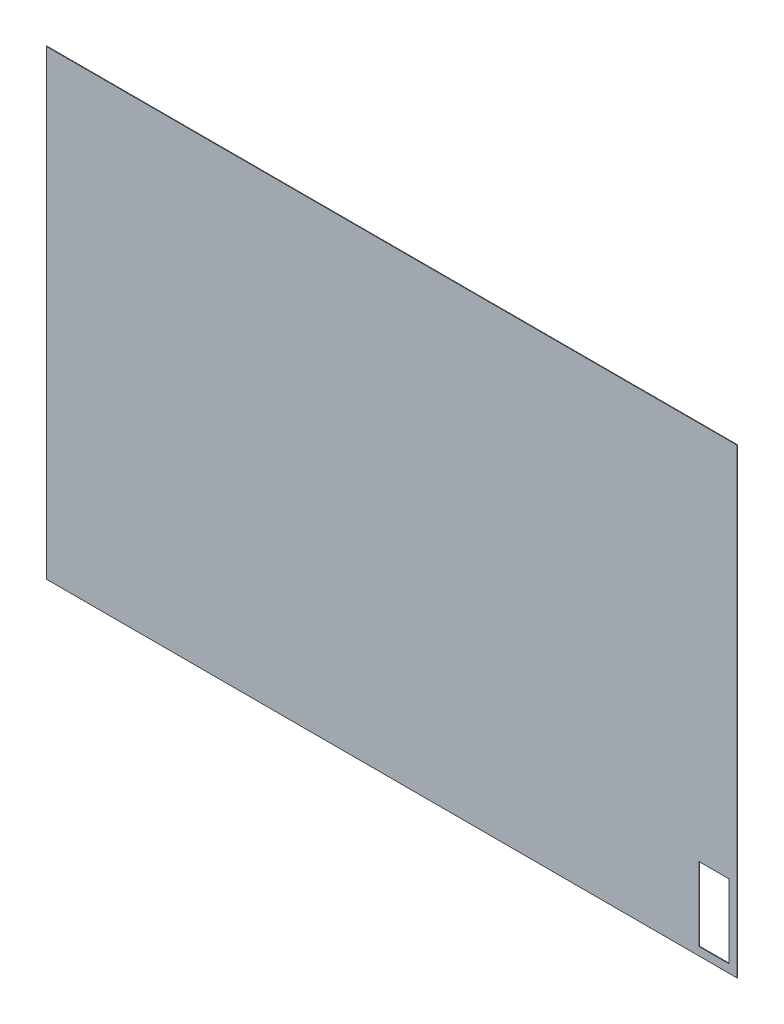
SolidWorks part; units mm, degrees
ref_plane "Front Plane" through (0, 0, 0) normal (0, 0, 1) x (1, 0, 0)
ref_plane "Top Plane" through (0, 0, 0) normal (0, 1, 0) x (1, 0, 0)
ref_plane "Right Plane" through (0, 0, 0) normal (1, 0, 0) x (0, 0, -1)
sketch "Sketch1" plane through (0, 0, 0) normal (0, 0, 1) x (1, 0, 0)
  line L1 (0, 0) -> (2500, 0)
  line L2 (0, 0) -> (0, 1670)
  line L3 (0, 1670) -> (2500, 1670)
  line L4 (2500, 0) -> (2500, 1670)
  line L5 (2470, 30) -> (2361.56, 30)
  line L6 (2470, 30) -> (2470, 296)
  line L7 (2470, 296) -> (2361.56, 296)
  line L8 (2361.56, 30) -> (2361.56, 296)
  dimension "D1" = 2500
  dimension "D2" = 1670
  dimension "D3" = 30
  dimension "D4" = 30
  dimension "D5" = 108.44
  dimension "D6" = 266
extrude "Boss-Extrude1" add sketch "Sketch1" along normal blind 2
